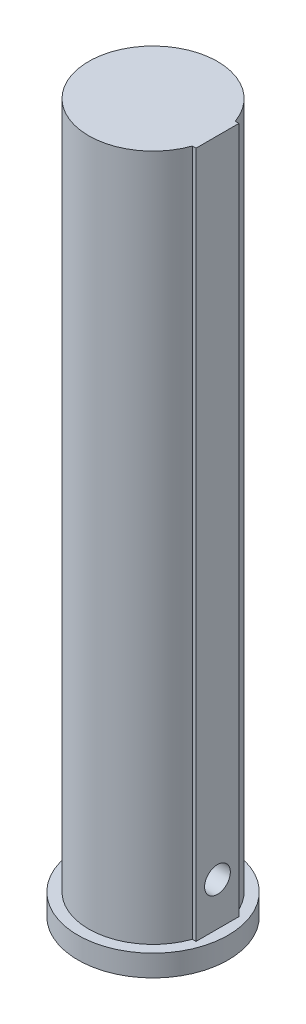
SolidWorks part; units mm, degrees
ref_plane "Front" through (0, 0, 0) normal (0, 0, 1) x (1, 0, 0)
ref_plane "Top" through (0, 0, 0) normal (0, 1, 0) x (1, 0, 0)
ref_plane "Right" through (0, 0, 0) normal (1, 0, 0) x (0, 0, -1)
sketch "Sketch1" plane through (0, 0, 0) normal (0, 1, 0) x (1, 0, 0)
  circle A0 centre (0, 0) radius 15
  dimension "D1" = 30
extrude "Boss-Extrude1" add sketch "Sketch1" along normal blind 160
sketch "Sketch2" plane through (0, 160, 0) normal (0, 1, 0) x (1, 0, 0)
  line L1 (14.1421, 5) -> (15, 5)
  line L2 (14.1421, 5) -> (14.1421, -5)
  line L3 (14.1421, -5) -> (15, -5)
  line L4 (15, 5) -> (15, -5)
  circle A0 centre (0, 0) radius 15 construction
  point P6 (14.0605, -5.2251)
  dimension "D1" = 10
extrude "Boss-Extrude2" add sketch "Sketch2" against normal up to surface (160 mm away) up to face at (0, 0, 15)
sketch "Sketch6" plane through (0, 0, 0) normal (0, -1, 0) x (1, 0, 0)
  circle A0 centre (0, 0) radius 17.5
  dimension "D1" = 35
extrude "Boss-Extrude4" add sketch "Sketch6" along normal blind 5
sketch "Sketch3" plane through (0, -5, 0) normal (0, -1, 0) x (1, 0, 0)
  line L0 (1.5, -1.3229) -> (1.5, 1.3229)
  arc A0 (1.5, 1.3229) -> (1.5, -1.3229) centre (0, 0) ccw
  dimension "D1" = 4
  dimension "D2" = 1.5
extrude "Cut-Extrude1" cut sketch "Sketch3" against normal blind 25
sketch "Sketch4" plane through (15, 0, 0) normal (1, 0, 0) x (0, 0, -1)
  line L0 (0, 10) -> (0, 0) construction
  circle A0 centre (0, 10) radius 1.5
  dimension "D2" = 3
  dimension "D1" = 10
extrude "Cut-Extrude2" cut sketch "Sketch4" against normal blind 15
sketch "Sketch7" plane through (0, 0, 0) normal (1, 0, 0) x (0, 0, -1)
  circle A0 centre (0, 10) radius 3
  dimension "D1" = 6
extrude "Cut-Extrude3" cut sketch "Sketch7" along normal up to next from offset 8
